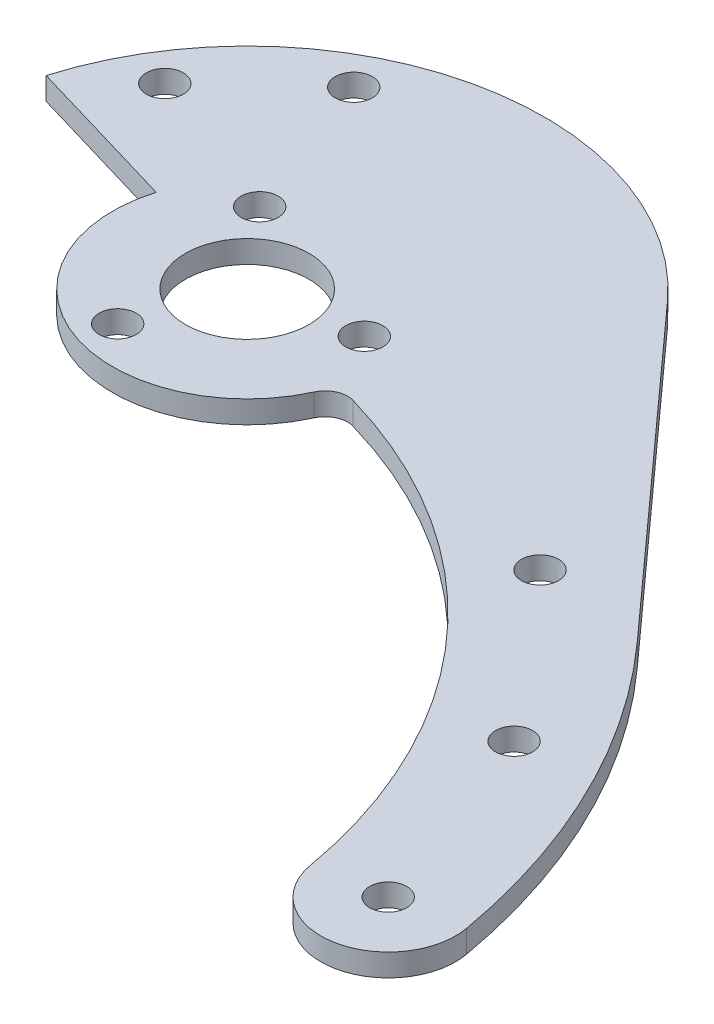
SolidWorks part; units mm, degrees
ref_plane "Спереди" through (0, 0, 0) normal (0, 0, 1) x (1, 0, 0)
ref_plane "Сверху" through (0, 0, 0) normal (0, 1, 0) x (1, 0, 0)
ref_plane "Справа" through (0, 0, 0) normal (1, 0, 0) x (0, 0, -1)
sketch "Эскиз1" plane through (0, 0, 0) normal (0, 1, 0) x (1, 0, 0)
  line L1 (0, -50) -> (53.1796, -40.623) construction
  line L2 (0, 0) -> (-15.6979, 16.81) construction
  line L3 (0, 0) -> (-19.5138, 12.1743) construction
  line L4 (0, -50) -> (0, 0) construction
  line L5 (0, -50) -> (46.7654, -23) construction
  line L6 (0, 0) -> (-3.0782, -8.4572) construction
  line L9 (-11.5083, 3.4) -> (-25.4141, 7.5083)
  line L10 (44.5417, -9.8) -> (19.6726, 17.755)
  line L11 (-5.754, 25.8678) -> (0, 0) construction
  arc A0 (-5.754, 25.8678) -> (-25.4141, 7.5083) centre (0, 0) ccw
  arc A1 (-5.754, 25.8678) -> (19.6726, 17.755) centre (0, 0) cw
  circle A2 centre (0, 0) radius 9 construction
  circle A3 centre (-5.7851, 6.8944) radius 1.65
  circle A4 centre (8.8633, 1.5628) radius 1.65
  circle A5 centre (0, 0) radius 5.5
  arc A6 (-4.9941, 22.4513) -> (-22.0575, 6.5167) centre (0, 0) ccw construction
  circle A7 centre (-3.0782, -8.4572) radius 1.65
  arc A8 (-11.5083, 3.4) -> (11.5083, -3.4) centre (0, 0) ccw
  circle A9 centre (-19.5138, 12.1743) radius 1.65
  circle A10 centre (-10.8123, 20.3001) radius 1.65
  arc A11 (47.2708, -41.6649) -> (11.5083, -3.4) centre (0, -50) ccw
  arc A12 (44.5417, -9.8) -> (59.0885, -39.5811) centre (0, -50) cw
  arc A13 (53.1796, -40.623) -> (34.7105, -8.6336) centre (0, -50) ccw construction
  arc A14 (59.0885, -39.5811) -> (47.2708, -41.6649) centre (53.1796, -40.623) cw
  circle A15 centre (53.1796, -40.623) radius 1.65
  circle A16 centre (46.7654, -23) radius 1.65
  circle A17 centre (34.7105, -8.6336) radius 1.65
  point P12 (0, 0)
  point P13 (0, 0)
  point P15 (-17.682, 14.7088)
  point P17 (0, 0)
  point P26 (0, 0)
  point P37 (0, -50)
  point P38 (-22.0575, 6.5167)
  dimension "D1" = 26.5
  dimension "D2" = 48
  dimension "D6" = 18
  dimension "D7" = 12
  dimension "D9" = 20
  dimension "D4" = 11
  dimension "D8" = 3.3
  dimension "D5" = 50
  dimension "D11" = 60
  dimension "D12" = 80
  dimension "D13" = 61
  dimension "D10" = 23
  dimension "D3" = 3
  dimension "D14" = 15
  dimension "D16" = 20
  dimension "D15" = 3
extrude "Основа" add sketch "Эскиз1" along normal blind 2
fillet "Скругление1" radius 2 1 edges at (11.5083, 1, 3.4)
